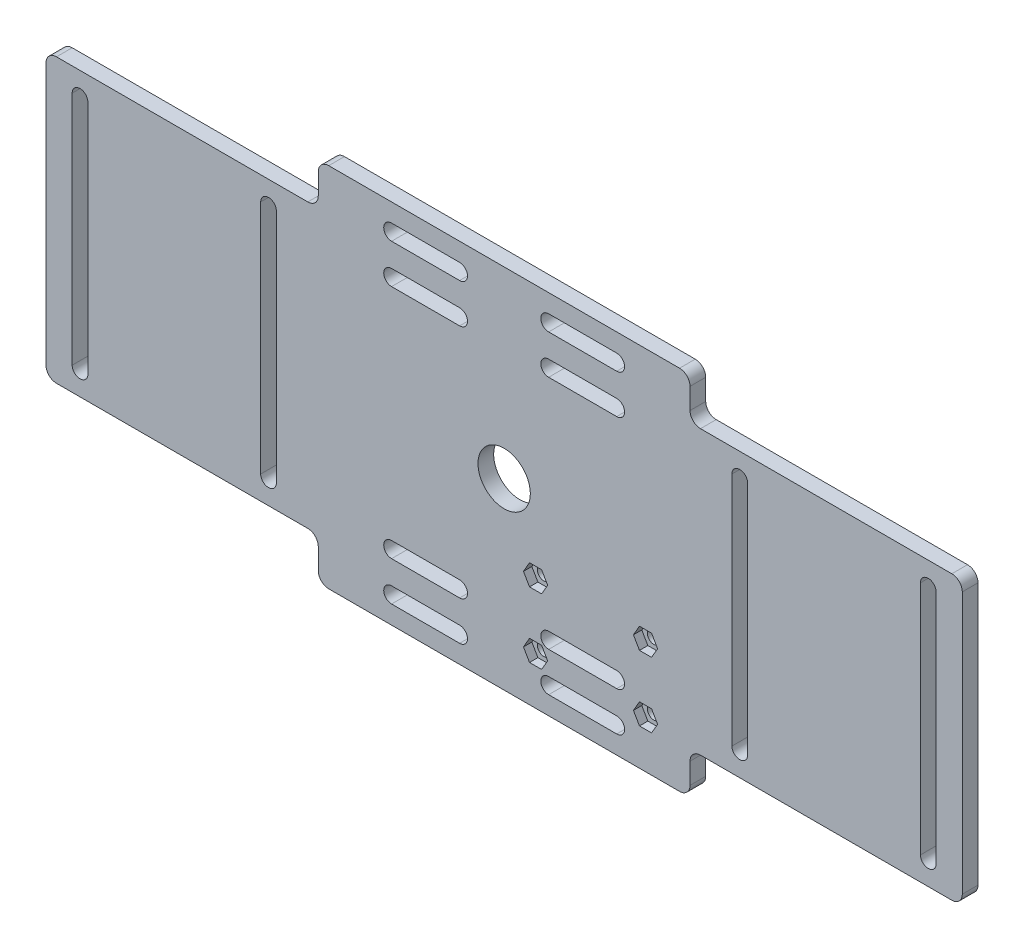
SolidWorks part; units mm, degrees
ref_plane "前基準面" through (0, 0, 0) normal (0, 0, 1) x (1, 0, 0)
ref_plane "上基準面" through (0, 0, 0) normal (0, 1, 0) x (1, 0, 0)
ref_plane "右基準面" through (0, 0, 0) normal (1, 0, 0) x (0, 0, -1)
sketch "草圖1" plane through (0, 0, 0) normal (0, 0, 1) x (1, 0, 0)
  line L0 (35.5, 33) -> (35.5, 29)
  line L1 (-33.5, 35) -> (33.5, 35)
  line L2 (-87.5, 25) -> (-87.5, -25)
  line L3 (-33.5, -35) -> (33.5, -35)
  line L4 (87.5, 25) -> (87.5, -25)
  line L5 (-87.5, 35) -> (87.5, -35) construction
  line L6 (-87.5, -35) -> (87.5, 35) construction
  line L7 (37.5, 27) -> (85.5, 27)
  line L8 (0, 71.4811) -> (0, -70.0061) construction
  line L9 (-113.0104, 0) -> (128.372, 0) construction
  line L10 (-37.5, 27) -> (-85.5, 27)
  line L11 (-35.5, 33) -> (-35.5, 29)
  line L12 (37.5, -27) -> (85.5, -27)
  line L13 (35.5, -33) -> (35.5, -29)
  line L14 (-35.5, -33) -> (-35.5, -29)
  line L15 (-37.5, -27) -> (-85.5, -27)
  arc A0 (35.5, 33) -> (33.5, 35) centre (33.5, 33) ccw
  arc A1 (37.5, 27) -> (35.5, 29) centre (37.5, 29) cw
  arc A2 (87.5, 25) -> (85.5, 27) centre (85.5, 25) ccw
  arc A3 (-87.5, 25) -> (-85.5, 27) centre (-85.5, 25) cw
  arc A4 (-37.5, 27) -> (-35.5, 29) centre (-37.5, 29) ccw
  arc A5 (-35.5, 33) -> (-33.5, 35) centre (-33.5, 33) cw
  arc A6 (87.5, -25) -> (85.5, -27) centre (85.5, -25) cw
  arc A7 (37.5, -27) -> (35.5, -29) centre (37.5, -29) ccw
  arc A8 (35.5, -33) -> (33.5, -35) centre (33.5, -33) cw
  arc A9 (-35.5, -33) -> (-33.5, -35) centre (-33.5, -33) ccw
  arc A10 (-37.5, -27) -> (-35.5, -29) centre (-37.5, -29) cw
  arc A11 (-87.5, -25) -> (-85.5, -27) centre (-85.5, -25) ccw
  point P0 (0, 0)
  point P13 (35.5, 27)
  point P29 (-35.5, 27)
  point P39 (35.5, -27)
  point P49 (-35.5, -27)
  dimension "D1" = 2
  dimension "D2" = 2
  dimension "D3" = 2
  dimension "D4" = 175
  dimension "D5" = 70
  dimension "D6" = 8
  dimension "D7" = 52
extrude "填料-伸長1" add sketch "草圖1" along normal blind 3
sketch "草圖2" plane through (0, 0, 3) normal (0, 0, 1) x (1, 0, 0)
  line L0 (-1000, 0) -> (49000, 0) construction
  line L1 (45, -986.1952) -> (45, 49013.8048) construction
  line L2 (-81, -962.7943) -> (-81, 49037.2057) construction
  line L3 (45, -22.5) -> (45, 22.5) construction
  line L4 (43.5, -22.5) -> (43.5, 22.5)
  line L5 (46.5, -22.5) -> (46.5, 22.5)
  line L6 (-45, -1000) -> (-45, 49000) construction
  line L7 (-45, -22.5) -> (-45, 22.5) construction
  line L8 (-46.5, -22.5) -> (-46.5, 22.5)
  line L9 (-43.5, -22.5) -> (-43.5, 22.5)
  line L10 (0, -1000) -> (0, 49000) construction
  line L11 (-1010.5287, 30) -> (48989.4713, 30) construction
  line L12 (-1007.193, -30) -> (48992.807, -30) construction
  line L13 (21.5, -30) -> (8.5, -30) construction
  line L16 (6, -996.0597) -> (6, 49003.9403) construction
  line L19 (81, -968.4295) -> (81, 49031.5705) construction
  line L20 (-81, -22.5) -> (-81, 22.5) construction
  line L21 (-82.5, -22.5) -> (-82.5, 22.5)
  line L22 (-79.5, -22.5) -> (-79.5, 22.5)
  line L23 (81, -22.5) -> (81, 22.5) construction
  line L24 (79.5, -22.5) -> (79.5, 22.5)
  line L25 (82.5, -22.5) -> (82.5, 22.5)
  line L26 (27, -997.4467) -> (27, 49002.5533) construction
  line L27 (-1014.4971, -26) -> (48985.5029, -26) construction
  line L28 (-1015.8254, -13.5) -> (48984.1746, -13.5) construction
  line L29 (-33.5, -35) -> (33.5, -35) construction
  line L30 (21.5, -31.5) -> (8.5, -31.5)
  line L33 (21.5, -28.5) -> (8.5, -28.5)
  line L34 (-21.5, -30) -> (-8.5, -30) construction
  line L35 (-21.5, -31.5) -> (-8.5, -31.5)
  line L36 (-21.5, -28.5) -> (-8.5, -28.5)
  line L37 (21.5, 30) -> (8.5, 30) construction
  line L38 (21.5, 31.5) -> (8.5, 31.5)
  line L39 (21.5, 28.5) -> (8.5, 28.5)
  line L40 (-21.5, 30) -> (-8.5, 30) construction
  line L41 (-21.5, 31.5) -> (-8.5, 31.5)
  line L42 (-21.5, 28.5) -> (-8.5, 28.5)
  line L43 (21.5, 22.5) -> (8.5, 22.5) construction
  line L44 (21.5, 24) -> (8.5, 24)
  line L45 (21.5, 21) -> (8.5, 21)
  line L46 (-21.5, 22.5) -> (-8.5, 22.5) construction
  line L47 (-21.5, 24) -> (-8.5, 24)
  line L48 (-21.5, 21) -> (-8.5, 21)
  line L49 (-21.5, -22.5) -> (-8.5, -22.5) construction
  line L50 (-21.5, -24) -> (-8.5, -24)
  line L51 (-21.5, -21) -> (-8.5, -21)
  line L52 (21.5, -22.5) -> (8.5, -22.5) construction
  line L53 (21.5, -24) -> (8.5, -24)
  line L54 (21.5, -21) -> (8.5, -21)
  arc A0 (43.5, -22.5) -> (46.5, -22.5) centre (45, -22.5) ccw
  arc A1 (46.5, 22.5) -> (43.5, 22.5) centre (45, 22.5) ccw
  arc A2 (-46.5, -22.5) -> (-43.5, -22.5) centre (-45, -22.5) ccw
  arc A3 (-43.5, 22.5) -> (-46.5, 22.5) centre (-45, 22.5) ccw
  arc A12 (-82.5, -22.5) -> (-79.5, -22.5) centre (-81, -22.5) ccw
  arc A13 (-79.5, 22.5) -> (-82.5, 22.5) centre (-81, 22.5) ccw
  arc A14 (79.5, -22.5) -> (82.5, -22.5) centre (81, -22.5) ccw
  arc A15 (82.5, 22.5) -> (79.5, 22.5) centre (81, 22.5) ccw
  circle A16 centre (0, 0) radius 5
  circle A17 centre (27, -13.5) radius 1.25
  circle A18 centre (6, -13.5) radius 1.25
  circle A19 centre (6, -26) radius 1.25
  circle A20 centre (27, -26) radius 1.25
  arc A23 (21.5, -31.5) -> (21.5, -28.5) centre (21.5, -30) ccw
  arc A24 (8.5, -28.5) -> (8.5, -31.5) centre (8.5, -30) ccw
  arc A25 (-21.5, -31.5) -> (-21.5, -28.5) centre (-21.5, -30) cw
  arc A26 (-8.5, -28.5) -> (-8.5, -31.5) centre (-8.5, -30) cw
  arc A27 (21.5, 31.5) -> (21.5, 28.5) centre (21.5, 30) cw
  arc A28 (8.5, 28.5) -> (8.5, 31.5) centre (8.5, 30) cw
  arc A29 (-21.5, 31.5) -> (-21.5, 28.5) centre (-21.5, 30) ccw
  arc A30 (-8.5, 28.5) -> (-8.5, 31.5) centre (-8.5, 30) ccw
  arc A31 (21.5, 24) -> (21.5, 21) centre (21.5, 22.5) cw
  arc A32 (8.5, 21) -> (8.5, 24) centre (8.5, 22.5) cw
  arc A33 (-21.5, 24) -> (-21.5, 21) centre (-21.5, 22.5) ccw
  arc A34 (-8.5, 21) -> (-8.5, 24) centre (-8.5, 22.5) ccw
  arc A35 (-21.5, -24) -> (-21.5, -21) centre (-21.5, -22.5) cw
  arc A36 (-8.5, -21) -> (-8.5, -24) centre (-8.5, -22.5) cw
  arc A37 (21.5, -24) -> (21.5, -21) centre (21.5, -22.5) ccw
  arc A38 (8.5, -21) -> (8.5, -24) centre (8.5, -22.5) ccw
  point P9 (45, 0)
  point P16 (-45, 0)
  point P31 (15, -30)
  point P47 (-81, 0)
  point P54 (81, 0)
  point P72 (-15, -30)
  point P81 (15, 30)
  point P88 (-15, 30)
  point P97 (15, 22.5)
  point P102 (-15, 22.5)
  point P110 (-15, -22.5)
  point P116 (15, -22.5)
  dimension "D10" = 1.5
  dimension "D20" = 10
  dimension "D21" = 2.5
  dimension "D27" = 7.5
  dimension "D2" = 45
  dimension "D3" = 3
  dimension "D4" = 90
  dimension "D5" = 45
  dimension "D6" = 3
  dimension "D7" = 45
  dimension "D8" = 60
  dimension "D9" = 30
  dimension "D11" = 13
  dimension "D12" = 12.5
  dimension "D13" = 21
  dimension "D14" = 162
  dimension "D15" = 81
  dimension "D16" = 3
  dimension "D17" = 45
  dimension "D18" = 45
  dimension "D19" = 3
  dimension "D22" = 9
  dimension "D23" = 6
  dimension "D24" = 8.5
  dimension "D25" = 2
  dimension "D28" = 7.5
  dimension "D26" = 2
extrude "除料-伸長1" cut sketch "草圖2" against normal through all
sketch "草圖3" plane through (0, 0, 3) normal (0, 0, 1) x (1, 0, 0)
  line L0 (29.3094, -26) -> (28.1547, -24)
  line L1 (8.3094, -26) -> (7.1547, -24)
  line L2 (7.1547, -24) -> (4.8453, -24)
  line L3 (4.8453, -24) -> (3.6906, -26)
  line L4 (3.6906, -26) -> (4.8453, -28)
  line L5 (4.8453, -28) -> (7.1547, -28)
  line L6 (7.1547, -28) -> (8.3094, -26)
  line L7 (28.1547, -24) -> (25.8453, -24)
  line L8 (25.8453, -24) -> (24.6906, -26)
  line L9 (24.6906, -26) -> (25.8453, -28)
  line L10 (25.8453, -28) -> (28.1547, -28)
  line L11 (28.1547, -28) -> (29.3094, -26)
  line L12 (29.3094, -13.5) -> (28.1547, -11.5)
  line L13 (28.1547, -11.5) -> (25.8453, -11.5)
  line L14 (25.8453, -11.5) -> (24.6906, -13.5)
  line L15 (24.6906, -13.5) -> (25.8453, -15.5)
  line L16 (25.8453, -15.5) -> (28.1547, -15.5)
  line L17 (28.1547, -15.5) -> (29.3094, -13.5)
  line L18 (8.3094, -13.5) -> (7.1547, -11.5)
  line L19 (7.1547, -11.5) -> (4.8453, -11.5)
  line L20 (4.8453, -11.5) -> (3.6906, -13.5)
  line L21 (3.6906, -13.5) -> (4.8453, -15.5)
  line L22 (4.8453, -15.5) -> (7.1547, -15.5)
  line L23 (7.1547, -15.5) -> (8.3094, -13.5)
  circle A0 centre (6, -26) radius 2 construction
  circle A3 centre (27, -26) radius 2 construction
  circle A4 centre (27, -13.5) radius 2 construction
  circle A5 centre (6, -13.5) radius 2 construction
  dimension "D1" = 4
  dimension "D2" = 2
  dimension "D3" = 2
extrude "除料-伸長2" cut sketch "草圖3" against normal blind 1.6
sketch "草圖4" plane through (0, 0, 0) normal (0, 0, -1) x (-1, 0, 0)
  circle A0 centre (-27, -13.5) radius 1.25
  circle A1 centre (-27, -26) radius 1.25
  circle A2 centre (-6, -13.5) radius 1.25
  circle A3 centre (-6, -26) radius 1.25
  circle A4 centre (-27, -13.5) radius 2
  circle A5 centre (-27, -26) radius 2
  circle A6 centre (-6, -13.5) radius 2
  circle A7 centre (-6, -26) radius 2
  dimension "D1" = 0.75
extrude "填料-伸長2" add sketch "草圖4" along normal blind 2
chamfer "導角1" distance 0.5 angle 30 4 edges at (25.75, -13.5, -2) (4.75, -13.5, -2) (4.75, -26, -2) (25.75, -26, -2)
